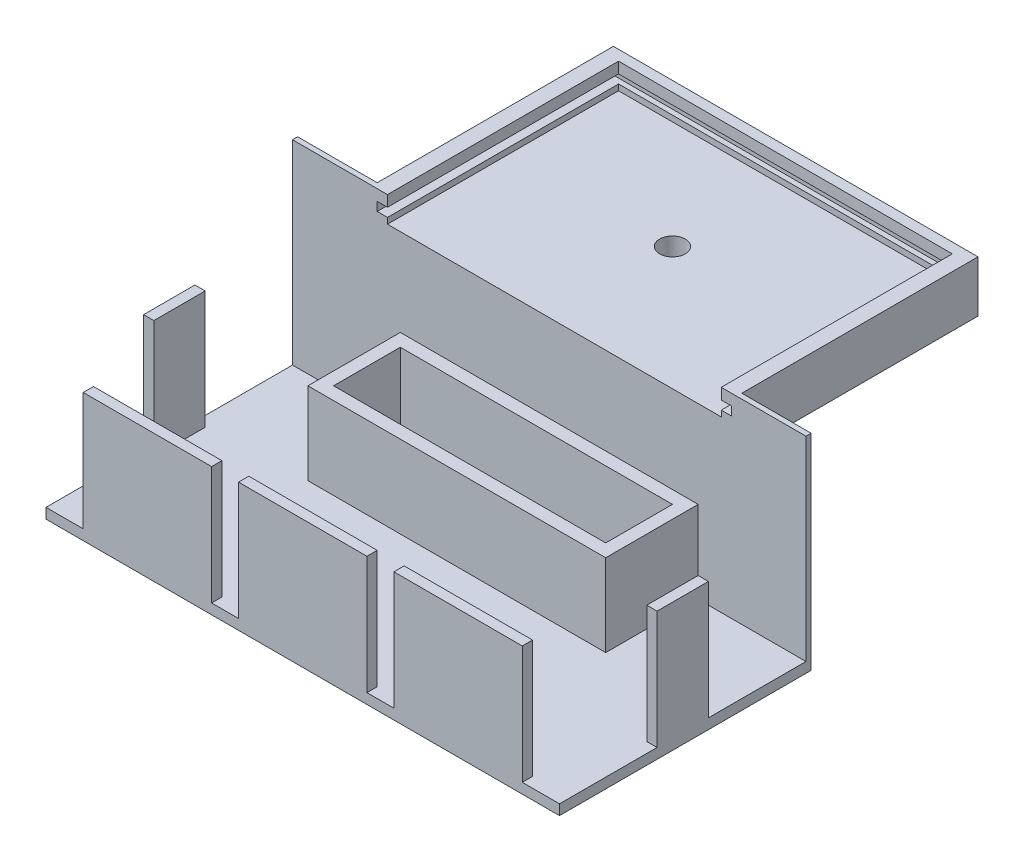
SolidWorks part; units mm, degrees
ref_plane "Alzado" through (0, 0, 0) normal (0, 0, 1) x (1, 0, 0)
ref_plane "Planta" through (0, 0, 0) normal (0, 1, 0) x (1, 0, 0)
ref_plane "Vista lateral" through (0, 0, 0) normal (1, 0, 0) x (0, 0, -1)
sketch "Croquis1" plane through (0, 0, 0) normal (0, 1, 0) x (1, 0, 0)
  line L1 (0, 0) -> (100, 0)
  line L2 (0, 0) -> (0, 95)
  line L3 (0, 95) -> (100, 95)
  line L4 (100, 0) -> (100, 95)
  dimension "D1" = 95
  dimension "D2" = 100
extrude "Saliente-Extruir1" add sketch "Croquis1" along normal blind 40
sketch "Croquis3" plane through (0, 0, 0) normal (0, -1, 0) x (1, 0, 0)
  line L1 (100, -95) -> (80, -95)
  line L2 (100, -95) -> (100, -49)
  line L3 (100, -49) -> (80, -49)
  line L4 (80, -95) -> (80, -49)
  line L5 (0, -95) -> (20, -95)
  line L6 (0, -95) -> (0, -49)
  line L7 (0, -49) -> (20, -49)
  line L8 (20, -95) -> (20, -49)
  dimension "D1" = 46
  dimension "D2" = 20
  dimension "D3" = 20
  dimension "D4" = 46
extrude "Cortar-Extruir1" cut sketch "Croquis3" against normal blind 30
sketch "Croquis4" plane through (0, 40, 0) normal (0, 1, 0) x (1, 0, 0)
  line L0 (50, 95) -> (50, 48) construction
  line L1 (100, 95) -> (0, 95) construction
  line L2 (0, 95) -> (0, 0) construction
  line L3 (2, 48) -> (98, 48)
  line L4 (2, 48) -> (2, 2)
  line L5 (2, 2) -> (98, 2)
  line L6 (98, 48) -> (98, 2)
  line L7 (0, 0) -> (100, 0) construction
  line L8 (100, 0) -> (100, 95) construction
  dimension "D1" = 47
  dimension "D2" = 2
  dimension "D3" = 2
  dimension "D4" = 2
  dimension "D5" = 47
extrude "Cortar-Extruir2" cut sketch "Croquis4" against normal blind 38
sketch "Croquis5" plane through (0, 40, 0) normal (0, 1, 0) x (1, 0, 0)
  line L0 (100, 95) -> (0, 95) construction
  line L1 (18.5, 93) -> (83.5, 93)
  line L2 (18.5, 93) -> (18.5, 26)
  line L3 (18.5, 26) -> (83.5, 26)
  line L4 (83.5, 93) -> (83.5, 26)
  line L6 (100, 0) -> (100, 95) construction
  dimension "D1" = 2
  dimension "D2" = 65
  dimension "D3" = 67
  dimension "D4" = 16.5
extrude "Cortar-Extruir3" cut sketch "Croquis5" against normal blind 5
sketch "Croquis7" plane through (0, 0, -48) normal (0, 0, 1) x (1, 0, 0)
  line L0 (18.5, 40) -> (2, 40) construction
  line L1 (16.5, 37.85) -> (85.5, 37.85)
  line L2 (16.5, 37.85) -> (16.5, 36.15)
  line L3 (16.5, 36.15) -> (85.5, 36.15)
  line L4 (85.5, 37.85) -> (85.5, 36.15)
  line L5 (83.5, 40) -> (83.5, 35) construction
  line L6 (18.5, 35) -> (18.5, 40) construction
  dimension "D1" = 2.15
  dimension "D2" = 1.7
  dimension "D3" = 2
  dimension "D4" = 2
extrude "Cortar-Extruir4" cut sketch "Croquis7" against normal blind 46
sketch "Croquis9" plane through (0, 40, 0) normal (0, 1, 0) x (1, 0, 0)
  line L0 (100, 95) -> (0, 95) construction
  line L1 (6, 85) -> (11, 85)
  line L2 (6, 85) -> (6, 70)
  line L3 (6, 70) -> (11, 70)
  line L4 (11, 85) -> (11, 70)
  line L5 (89, 85) -> (94, 85)
  line L6 (89, 85) -> (89, 70)
  line L7 (89, 70) -> (94, 70)
  line L8 (94, 85) -> (94, 70)
  line L9 (0, 95) -> (0, 0) construction
  line L10 (100, 0) -> (100, 95) construction
  dimension "D1" = 10
  dimension "D2" = 15
  dimension "D3" = 6
  dimension "D4" = 5
  dimension "D5" = 10
  dimension "D6" = 5
  dimension "D7" = 6
  dimension "D8" = 15
extrude "Cortar-Extruir6" cut sketch "Croquis9" against normal blind 10
sketch "Croquis10" plane through (0, 35, 0) normal (0, 1, 0) x (1, 0, 0)
  line L0 (100, 95) -> (0, 95) construction
  line L1 (0, 95) -> (0, 0) construction
  circle A0 centre (50, 72) radius 2.5
  dimension "D1" = 5
  dimension "D3" = 50
  dimension "D2" = 23
extrude "Cortar-Extruir8" cut sketch "Croquis10" against normal through all contours A0
sketch "Croquis11" plane through (80, 0, 0) normal (1, 0, 0) x (0, 0, -1)
  line L1 (49, 30) -> (95, 30)
  line L2 (49, 30) -> (49, 0)
  line L3 (49, 0) -> (95, 0)
  line L4 (95, 30) -> (95, 0)
extrude "Cortar-Extruir9" cut sketch "Croquis11" against normal through all
sketch "Croquis12" plane through (0, 40, 0) normal (0, 1, 0) x (1, 0, 0)
  line L0 (100, 95) -> (0, 95) construction
  line L1 (86.5, 95) -> (100, 95)
  line L2 (86.5, 95) -> (86.5, 49)
  line L3 (86.5, 49) -> (100, 49)
  line L4 (100, 95) -> (100, 49)
  line L5 (83.5, 48) -> (83.5, 93) construction
  line L6 (18.5, 93) -> (18.5, 48) construction
  line L7 (0, 95) -> (15.5, 95)
  line L8 (0, 95) -> (0, 49)
  line L9 (0, 49) -> (15.5, 49)
  line L10 (15.5, 95) -> (15.5, 49)
  dimension "D1" = 3
  dimension "D2" = 3
extrude "Cortar-Extruir10" cut sketch "Croquis12" against normal through all
sketch "Croquis13" plane through (0, 0, 0) normal (0, 0, 1) x (1, 0, 0)
  line L15 (2, 40) -> (98, 40)
  line L20 (7.25, 25) -> (32.25, 25)
  line L24 (37.5, 25) -> (62.5, 25)
  line L28 (67.75, 25) -> (92.75, 25)
  line L35 (0, 40) -> (100, 40) construction
  line L37 (2, 40) -> (2, 2)
  line L38 (98, 40) -> (98, 2)
  line L39 (2, 2) -> (7.25, 2)
  line L40 (7.25, 2) -> (7.25, 25)
  line L41 (32.25, 25) -> (32.25, 2)
  line L42 (32.25, 2) -> (37.5, 2)
  line L43 (37.5, 2) -> (37.5, 25)
  line L44 (62.5, 25) -> (62.5, 2)
  line L45 (62.5, 2) -> (67.75, 2)
  line L46 (67.75, 2) -> (67.75, 25)
  line L47 (92.75, 25) -> (92.75, 2)
  line L48 (92.75, 2) -> (98, 2)
  dimension "D2" = 25
  dimension "D3" = 25
  dimension "D4" = 25
  dimension "D5" = 23
  dimension "D6" = 5.25
  dimension "D7" = 5.25
  dimension "D8" = 5.25
  dimension "D9" = 5.25
  dimension "D11" = 38
  dimension "D12" = 38
sketch "Croquis14" plane through (100, 0, 0) normal (1, 0, 0) x (0, 0, -1)
  line L0 (19, 25) -> (29, 25)
  line L2 (19, 25) -> (19, 2)
  line L8 (0, 40) -> (48, 40)
  line L9 (0, 40) -> (49, 40) construction
  line L10 (48, 40) -> (48, 2)
  line L11 (48, 2) -> (29, 2)
  line L12 (29, 2) -> (29, 25)
  line L13 (19, 2) -> (0, 2)
  line L14 (0, 40) -> (0, 0) construction
  line L15 (0, 2) -> (0, 40)
  line L16 (0, 0) -> (49, 0) construction
  point P2 (24, 25)
  dimension "D1" = 10
  dimension "D2" = 48
  dimension "D3" = 2
  dimension "D4" = 2
  dimension "D5" = 23
  dimension "D6" = 24
extrude "Cortar-Extruir13" cut sketch "Croquis14" against normal blind 2
sketch "Croquis15" plane through (0, 0, 0) normal (-1, 0, 0) x (0, 0, 1)
  line L2 (-48, 2) -> (-48, 40)
  line L4 (-29, 25) -> (-19, 25)
  line L10 (-49, 0) -> (0, 0) construction
  line L11 (0, 40) -> (0, 2)
  line L12 (0, 40) -> (0, 0) construction
  line L13 (0, 2) -> (-19, 2)
  line L14 (-19, 2) -> (-19, 25)
  line L16 (-29, 2) -> (-29, 25)
  line L17 (0, 40) -> (-48, 40)
  line L18 (-49, 40) -> (0, 40) construction
  line L19 (-29, 2) -> (-48, 2)
  point P2 (-24, 25)
  dimension "D1" = 38
  dimension "D2" = 10
  dimension "D3" = 48
  dimension "D4" = 24
  dimension "D5" = 23
  dimension "D6" = 2
extrude "Cortar-Extruir14" cut sketch "Croquis15" against normal blind 2
extrude "Cortar-Extruir15" cut sketch "Croquis13" against normal blind 2
sketch "Croquis16" plane through (0, 2, 0) normal (0, 1, 0) x (1, 0, 0)
  line L0 (100, 48) -> (0, 48) construction
  line L1 (21, 48) -> (79, 48)
  line L2 (21, 48) -> (21, 30)
  line L3 (21, 30) -> (79, 30)
  line L4 (79, 48) -> (79, 30)
  line L5 (0, 48) -> (0, 29) construction
  point P6 (50, 48)
  dimension "D1" = 58
  dimension "D2" = 18
  dimension "D3" = 50
extrude "Saliente-Extruir2" add sketch "Croquis16" along normal blind 16
sketch "Croquis17" plane through (0, 18, 0) normal (0, 1, 0) x (1, 0, 0)
  line L0 (21, 48) -> (21, 30) construction
  line L1 (23.5, 45.5) -> (76.5, 45.5)
  line L2 (23.5, 45.5) -> (23.5, 32.5)
  line L3 (23.5, 32.5) -> (76.5, 32.5)
  line L4 (76.5, 45.5) -> (76.5, 32.5)
  line L5 (79, 30) -> (79, 48) construction
  line L6 (21, 30) -> (79, 30) construction
  line L7 (79, 48) -> (21, 48) construction
  dimension "D1" = 2.5
  dimension "D2" = 2.5
  dimension "D3" = 2.5
  dimension "D4" = 2.5
extrude "Cortar-Extruir16" cut sketch "Croquis17" against normal blind 16
